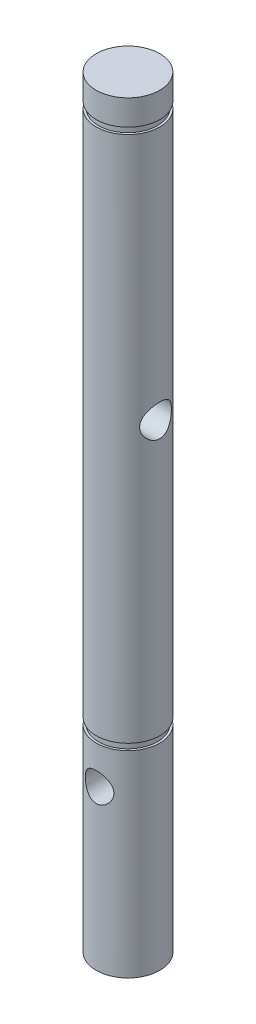
SolidWorks part; units mm, degrees
material "6061 Alloy"
ref_plane "Front Plane" through (0, 0, 0) normal (0, 0, 1) x (1, 0, 0)
ref_plane "Top Plane" through (0, 0, 0) normal (0, 1, 0) x (1, 0, 0)
ref_plane "Right Plane" through (0, 0, 0) normal (1, 0, 0) x (0, 0, -1)
sketch "Sketch1" plane through (0, 0, 0) normal (0, 1, 0) x (1, 0, 0)
  circle A0 centre (0, 0) radius 5
  dimension "D1" = 10
extrude "Boss-Extrude1" add sketch "Sketch1" along normal mid plane 120
sketch "Sketch3" plane through (0, 0, 0) normal (0, 0, 1) x (1, 0, 0)
  line L0 (-5, -60) -> (5, -60) construction
  circle A0 centre (0, -35) radius 2.25
  dimension "D1" = 4.5
  dimension "D2" = 25
extrude "Cut-Extrude2" cut sketch "Sketch3" against normal through all both and the other way through all
ref_plane "Plane1" through (0, -28, 0) normal (0, -1, 0) x (-1, 0, 0)
sketch "Sketch4" plane through (0, -28, 0) normal (0, -1, 0) x (-1, 0, 0)
  circle A0 centre (0, 0) radius 4.65
  circle A1 centre (0, 0) radius 5 construction
  circle A2 centre (0, 0) radius 5
  dimension "D1" = 9.3
extrude "Cut-Extrude3" cut sketch "Sketch4" along normal blind 1
ref_plane "Plane2" through (0, 55, 0) normal (0, 1, 0) x (1, 0, 0)
sketch "Sketch5" plane through (0, 55, 0) normal (0, 1, 0) x (1, 0, 0)
  circle A0 centre (0, 0) radius 4.65 construction
  circle A1 centre (0, 0) radius 5 construction
  circle A2 centre (0, 0) radius 4.65
  circle A3 centre (0, 0) radius 5
extrude "Cut-Extrude4" cut sketch "Sketch5" along normal blind 1
sketch "Sketch6" plane through (0, 0, 0) normal (1, 0, 0) x (0, 0, -1)
  circle A0 centre (0, 15) radius 2.5
  dimension "D1" = 5
  dimension "D2" = 15
extrude "Cut-Extrude5" cut sketch "Sketch6" against normal through all both and the other way through all
